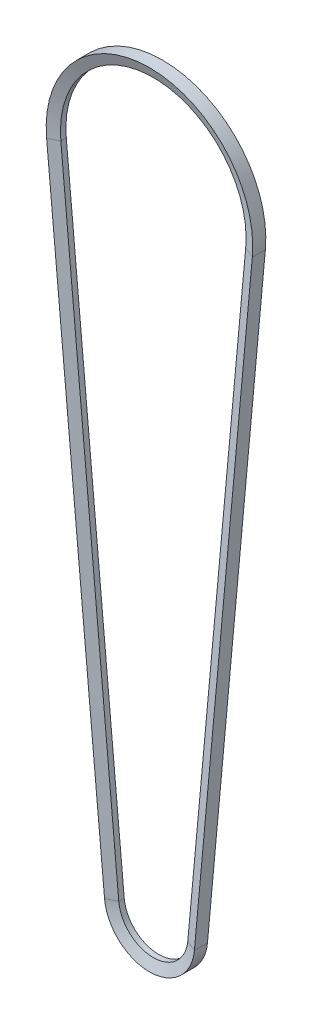
SolidWorks part; units mm, degrees
ref_plane "Front Plane" through (0, 0, 0) normal (0, 0, 1) x (1, 0, 0)
ref_plane "Top Plane" through (0, 0, 0) normal (0, 1, 0) x (1, 0, 0)
ref_plane "Right Plane" through (0, 0, 0) normal (1, 0, 0) x (0, 0, -1)
sketch "Sketch2" plane through (0, 0, 0) normal (0, 0, 1) x (1, 0, 0)
  line L0 (0, 0) -> (1, 0) construction
  line L1 (0, 0) -> (0, 1) construction
  line L2 (-25.3927, -2.3373) -> (-69.7053, 479.0839)
  line L3 (69.7053, 479.0839) -> (25.3927, -2.3373)
  arc A0 (25.3927, -2.3373) -> (-25.3927, -2.3373) centre (0, 0) cw
  arc A1 (-69.7053, 479.0839) -> (69.7053, 479.0839) centre (0, 485.5) cw
ref_plane "Plane1" through (69.7053, 479.0839, 0) normal (-0.0917, -0.9958, 0) x (-0.9958, 0.0917, 0)
sketch "Sketch3" plane through (69.7053, 479.0839, 0) normal (-0.0917, -0.9958, 0) x (-0.9958, 0.0917, 0)
  line L0 (-1, -2.0882) -> (-1, 2.0882)
  line L1 (-1, 2.0882) -> (-9, 5)
  line L2 (-9, 5) -> (-9, -5)
  line L3 (-9, -5) -> (-1, -2.0882)
  line L4 (-1, 0) -> (-3.0463, 0) construction
  line L5 (0, 0) -> (-0.1729, 0) construction
  point P4 (-1, 0)
  point P6 (0, 0)
  dimension "D1" = 1
  dimension "D2" = 8
  dimension "D3" = 10
  dimension "D4" = 40
sweep "Sweep1" add profiles "Sketch3" path "Sketch2"
